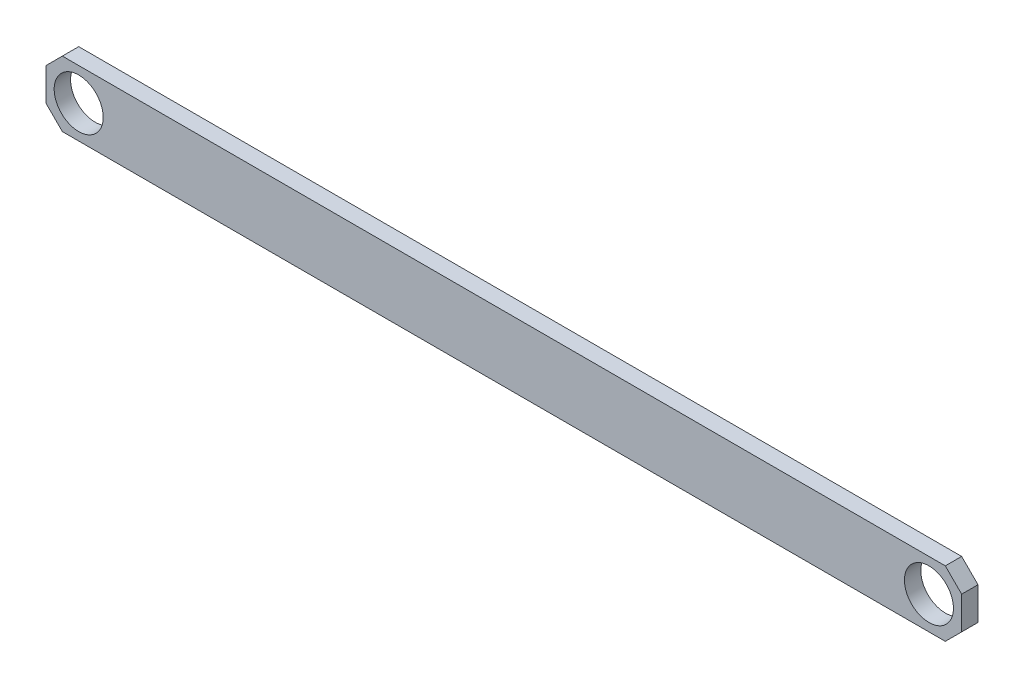
SolidWorks part; units mm, degrees
ref_plane "Front" through (0, 0, 0) normal (0, 0, 1) x (1, 0, 0)
ref_plane "Top" through (0, 0, 0) normal (0, 1, 0) x (1, 0, 0)
ref_plane "Right" through (0, 0, 0) normal (1, 0, 0) x (0, 0, -1)
other "Configuration Table"
sketch "Sketch1" plane through (0, 0, 0) normal (0, 0, 1) x (1, 0, 0)
  line L0 (0, 6.35) -> (27.8068, 6.35) construction
  line L1 (0, 0) -> (177.8, 0)
  line L2 (0, 0) -> (0, 12.7)
  line L3 (0, 12.7) -> (177.8, 12.7)
  line L4 (177.8, 0) -> (177.8, 12.7)
  line L5 (88.9, 0) -> (88.9, -44.6153) construction
  circle A0 centre (6.35, 6.35) radius 4.7625
  circle A1 centre (171.45, 6.35) radius 4.7625
  dimension "D3" = 9.525
  dimension "D4" = 6.35
  dimension "D1" = 12.7
  dimension "D2" = 177.8
extrude "Base-Extrude" add sketch "Sketch1" along normal blind 3.175
chamfer "Chamfer1" distance 3.175 angle 45 4 edges at (0, 12.7, 1.5875) (177.8, 12.7, 1.5875) (177.8, 0, 1.5875) (0, 0, 1.5875)
